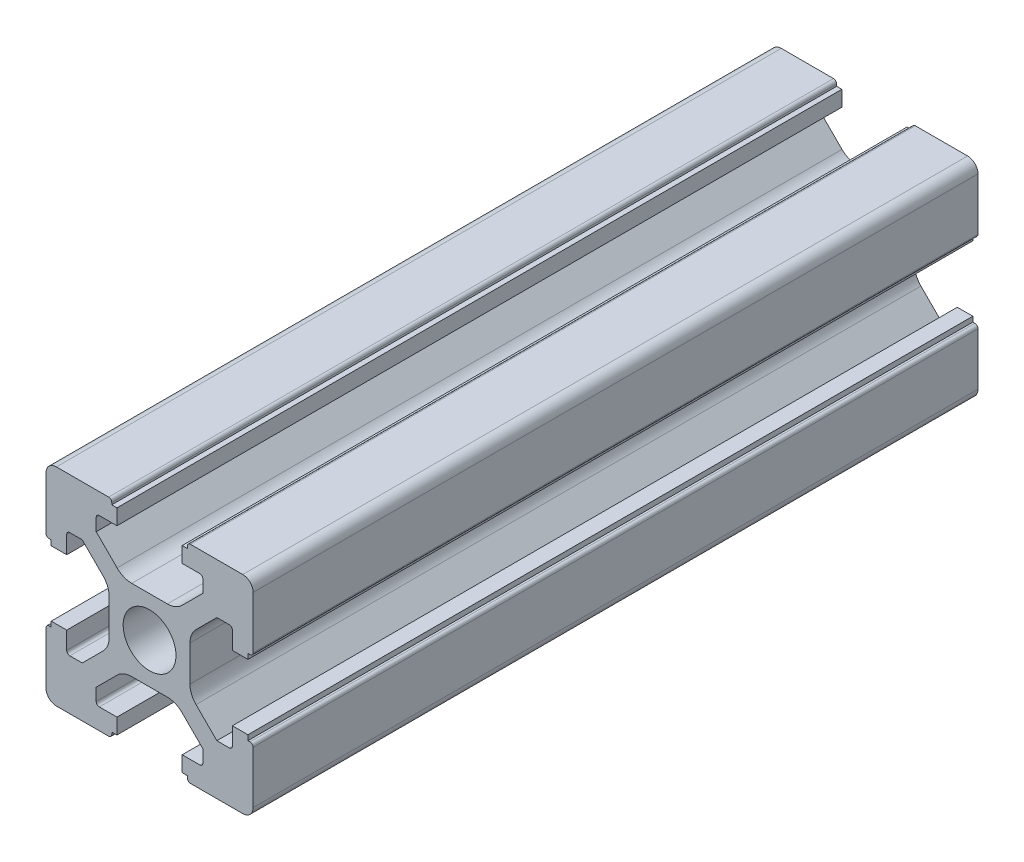
SolidWorks part; units mm, degrees
ref_plane "前视基准面" through (0, 0, 0) normal (0, 0, 1) x (1, 0, 0)
ref_plane "上视基准面" through (0, 0, 0) normal (0, 1, 0) x (1, 0, 0)
ref_plane "右视基准面" through (0, 0, 0) normal (1, 0, 0) x (0, 0, -1)
sketch "草图1" plane through (0, 0, 0) normal (0, 0, 1) x (1, 0, 0)
  line L1 (-10, -9) -> (-10, -3.95)
  line L3 (-9.7, -3.65) -> (-9.5, -3.65)
  line L5 (-9.5, -3.65) -> (-9.5, -3.15)
  line L7 (-9.5, -3.15) -> (-8, -3.15)
  line L9 (-8, -3.15) -> (-8, -4.85)
  line L11 (-7.7, -5.15) -> (-6.5, -5.15)
  line L13 (-6.5, -5.15) -> (-4.4858, -3.1358)
  line L15 (-3.9, -1.7216) -> (-3.9, 1.7216)
  line L17 (-6.5, 5.15) -> (-4.4858, 3.1358)
  line L19 (-7.7, 5.15) -> (-6.5, 5.15)
  line L21 (-8, 3.15) -> (-8, 4.85)
  line L23 (-9.5, 3.15) -> (-8, 3.15)
  line L25 (-9.5, 3.65) -> (-9.5, 3.15)
  line L27 (-9.7, 3.65) -> (-9.5, 3.65)
  line L29 (-10, 9) -> (-10, 3.95)
  line L31 (-9, 10) -> (-3.95, 10)
  line L33 (-3.65, 9.7) -> (-3.65, 9.5)
  line L35 (-3.65, 9.5) -> (-3.15, 9.5)
  line L37 (-3.15, 9.5) -> (-3.15, 8)
  line L39 (-3.15, 8) -> (-4.85, 8)
  line L41 (-5.15, 7.7) -> (-5.15, 6.5)
  line L43 (-5.15, 6.5) -> (-3.1358, 4.4858)
  line L45 (1.7216, 3.9) -> (-1.7216, 3.9)
  line L47 (5.15, 6.5) -> (3.1358, 4.4858)
  line L49 (5.15, 7.7) -> (5.15, 6.5)
  line L51 (3.15, 8) -> (4.85, 8)
  line L53 (3.15, 9.5) -> (3.15, 8)
  line L55 (3.65, 9.5) -> (3.15, 9.5)
  line L57 (3.65, 9.7) -> (3.65, 9.5)
  line L59 (9, 10) -> (3.95, 10)
  line L61 (10, 9) -> (10, 3.95)
  line L63 (9.7, 3.65) -> (9.5, 3.65)
  line L65 (9.5, 3.65) -> (9.5, 3.15)
  line L67 (9.5, 3.15) -> (8, 3.15)
  line L69 (8, 3.15) -> (8, 4.85)
  line L71 (7.7, 5.15) -> (6.5, 5.15)
  line L73 (6.5, 5.15) -> (4.4858, 3.1358)
  line L75 (3.9, 1.7216) -> (3.9, -1.7216)
  line L77 (6.5, -5.15) -> (4.4858, -3.1358)
  line L79 (7.7, -5.15) -> (6.5, -5.15)
  line L81 (8, -3.15) -> (8, -4.85)
  line L83 (9.5, -3.15) -> (8, -3.15)
  line L85 (9.5, -3.65) -> (9.5, -3.15)
  line L87 (9.7, -3.65) -> (9.5, -3.65)
  line L89 (10, -9) -> (10, -3.95)
  line L91 (9, -10) -> (3.95, -10)
  line L93 (3.65, -9.7) -> (3.65, -9.5)
  line L95 (3.65, -9.5) -> (3.15, -9.5)
  line L97 (3.15, -9.5) -> (3.15, -8)
  line L99 (3.15, -8) -> (4.85, -8)
  line L101 (5.15, -7.7) -> (5.15, -6.5)
  line L103 (5.15, -6.5) -> (3.1358, -4.4858)
  line L105 (-1.7216, -3.9) -> (1.7216, -3.9)
  line L107 (-5.15, -6.5) -> (-3.1358, -4.4858)
  line L109 (-5.15, -7.7) -> (-5.15, -6.5)
  line L111 (-3.15, -8) -> (-4.85, -8)
  line L113 (-3.15, -9.5) -> (-3.15, -8)
  line L115 (-3.65, -9.5) -> (-3.15, -9.5)
  line L117 (-3.65, -9.7) -> (-3.65, -9.5)
  line L119 (-9, -10) -> (-3.95, -10)
  ellipse E1 centre (0, 0) end of major axis (2.55, 0) minor radius 2.55
  ellipse E3 centre (-9, -9) end of major axis (-10, -9) minor radius 1 (-10, -9) -> (-9, -10) ccw
  ellipse E5 centre (-9.7, -3.95) end of major axis (-10, -3.95) minor radius 0.3 (-9.7, -3.65) -> (-10, -3.95) ccw
  ellipse E7 centre (-7.7, -4.85) end of major axis (-7.4, -4.85) minor radius 0.3 (-8, -4.85) -> (-7.7, -5.15) ccw
  ellipse E9 centre (-5.9, -1.7216) end of major axis (-5.9, -3.7216) minor radius 2 (-4.4858, -3.1358) -> (-3.9, -1.7216) ccw
  ellipse E11 centre (-5.9, 1.7216) end of major axis (-3.9, 1.7216) minor radius 2 (-3.9, 1.7216) -> (-4.4858, 3.1358) ccw
  ellipse E13 centre (-7.7, 4.85) end of major axis (-7.4, 4.85) minor radius 0.3 (-7.7, 5.15) -> (-8, 4.85) ccw
  ellipse E15 centre (-9.7, 3.95) end of major axis (-9.4, 3.95) minor radius 0.3 (-10, 3.95) -> (-9.7, 3.65) ccw
  ellipse E17 centre (-9, 9) end of major axis (-10, 9) minor radius 1 (-9, 10) -> (-10, 9) ccw
  ellipse E19 centre (-3.95, 9.7) end of major axis (-3.65, 9.7) minor radius 0.3 (-3.65, 9.7) -> (-3.95, 10) ccw
  ellipse E21 centre (-4.85, 7.7) end of major axis (-4.55, 7.7) minor radius 0.3 (-4.85, 8) -> (-5.15, 7.7) ccw
  ellipse E23 centre (-1.7216, 5.9) end of major axis (0.2784, 5.9) minor radius 2 (-3.1358, 4.4858) -> (-1.7216, 3.9) ccw
  ellipse E25 centre (1.7216, 5.9) end of major axis (-0.2784, 5.9) minor radius 2 (1.7216, 3.9) -> (3.1358, 4.4858) ccw
  ellipse E27 centre (4.85, 7.7) end of major axis (4.85, 8) minor radius 0.3 (5.15, 7.7) -> (4.85, 8) ccw
  ellipse E29 centre (3.95, 9.7) end of major axis (3.95, 10) minor radius 0.3 (3.95, 10) -> (3.65, 9.7) ccw
  ellipse E31 centre (9, 9) end of major axis (10, 9) minor radius 1 (10, 9) -> (9, 10) ccw
  ellipse E33 centre (9.7, 3.95) end of major axis (10, 3.95) minor radius 0.3 (9.7, 3.65) -> (10, 3.95) ccw
  ellipse E35 centre (7.7, 4.85) end of major axis (7.4, 4.85) minor radius 0.3 (8, 4.85) -> (7.7, 5.15) ccw
  ellipse E37 centre (5.9, 1.7216) end of major axis (7.9, 1.7216) minor radius 2 (4.4858, 3.1358) -> (3.9, 1.7216) ccw
  ellipse E39 centre (5.9, -1.7216) end of major axis (7.9, -1.7216) minor radius 2 (3.9, -1.7216) -> (4.4858, -3.1358) ccw
  ellipse E41 centre (7.7, -4.85) end of major axis (8, -4.85) minor radius 0.3 (7.7, -5.15) -> (8, -4.85) ccw
  ellipse E43 centre (9.7, -3.95) end of major axis (10, -3.95) minor radius 0.3 (10, -3.95) -> (9.7, -3.65) ccw
  ellipse E45 centre (9, -9) end of major axis (10, -9) minor radius 1 (9, -10) -> (10, -9) ccw
  ellipse E47 centre (3.95, -9.7) end of major axis (3.95, -9.4) minor radius 0.3 (3.65, -9.7) -> (3.95, -10) ccw
  ellipse E49 centre (4.85, -7.7) end of major axis (4.85, -7.4) minor radius 0.3 (4.85, -8) -> (5.15, -7.7) ccw
  ellipse E51 centre (1.7216, -5.9) end of major axis (1.7216, -3.9) minor radius 2 (3.1358, -4.4858) -> (1.7216, -3.9) ccw
  ellipse E53 centre (-1.7216, -5.9) end of major axis (-1.7216, -3.9) minor radius 2 (-1.7216, -3.9) -> (-3.1358, -4.4858) ccw
  ellipse E55 centre (-4.85, -7.7) end of major axis (-4.55, -7.7) minor radius 0.3 (-5.15, -7.7) -> (-4.85, -8) ccw
  ellipse E57 centre (-3.95, -9.7) end of major axis (-3.65, -9.7) minor radius 0.3 (-3.95, -10) -> (-3.65, -9.7) ccw
  dimension "D2" = 20
extrude "凸台-拉伸1" add sketch "草图1" along normal blind 70
